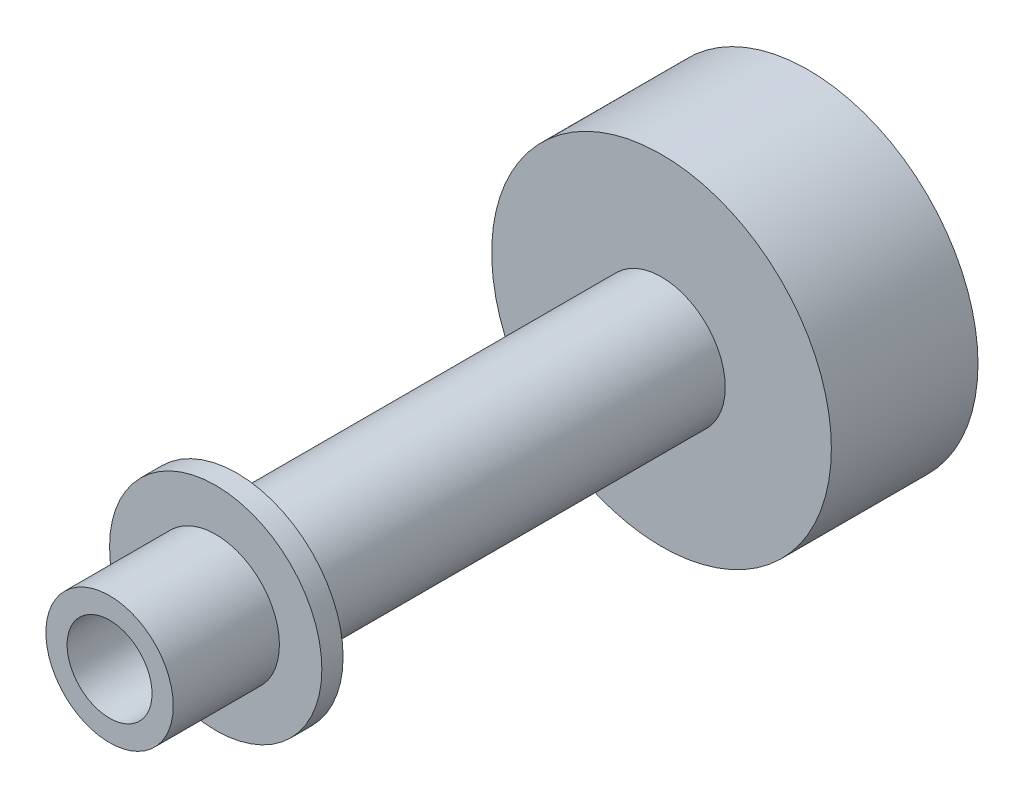
SolidWorks part; units mm, degrees
material "Ductile Iron"
ref_plane "Front Plane" through (0, 0, 0) normal (0, 0, 1) x (1, 0, 0)
ref_plane "Top Plane" through (0, 0, 0) normal (0, 1, 0) x (1, 0, 0)
ref_plane "Right Plane" through (0, 0, 0) normal (1, 0, 0) x (0, 0, -1)
sketch "Sketch2" plane through (0, 0, 0) normal (1, 0, 0) x (0, 0, -1)
  line L0 (0, 4) -> (0, 6)
  line L1 (0, 6) -> (10, 6)
  line L2 (10, 6) -> (10, 10)
  line L4 (52, 6) -> (52, 16)
  line L5 (52, 16) -> (65.814, 16)
  line L6 (65.814, 16) -> (65.814, 4)
  line L7 (65.814, 4) -> (0, 4)
  line L8 (10, 10) -> (12, 10)
  line L9 (12, 10) -> (12, 6)
  line L10 (12, 6) -> (52, 6)
  line L12 (0, 0) -> (109.9412, 0) construction
  point P2 (0, 0)
  dimension "D1" = 2
  dimension "D2" = 10
  dimension "D3" = 4
  dimension "D4" = 2
  dimension "D5" = 10
  dimension "D6" = 13.814
  dimension "D7" = 40
  dimension "D8" = 6
revolve "Revolve1" add sketch "Sketch2" angle 360 about L12
